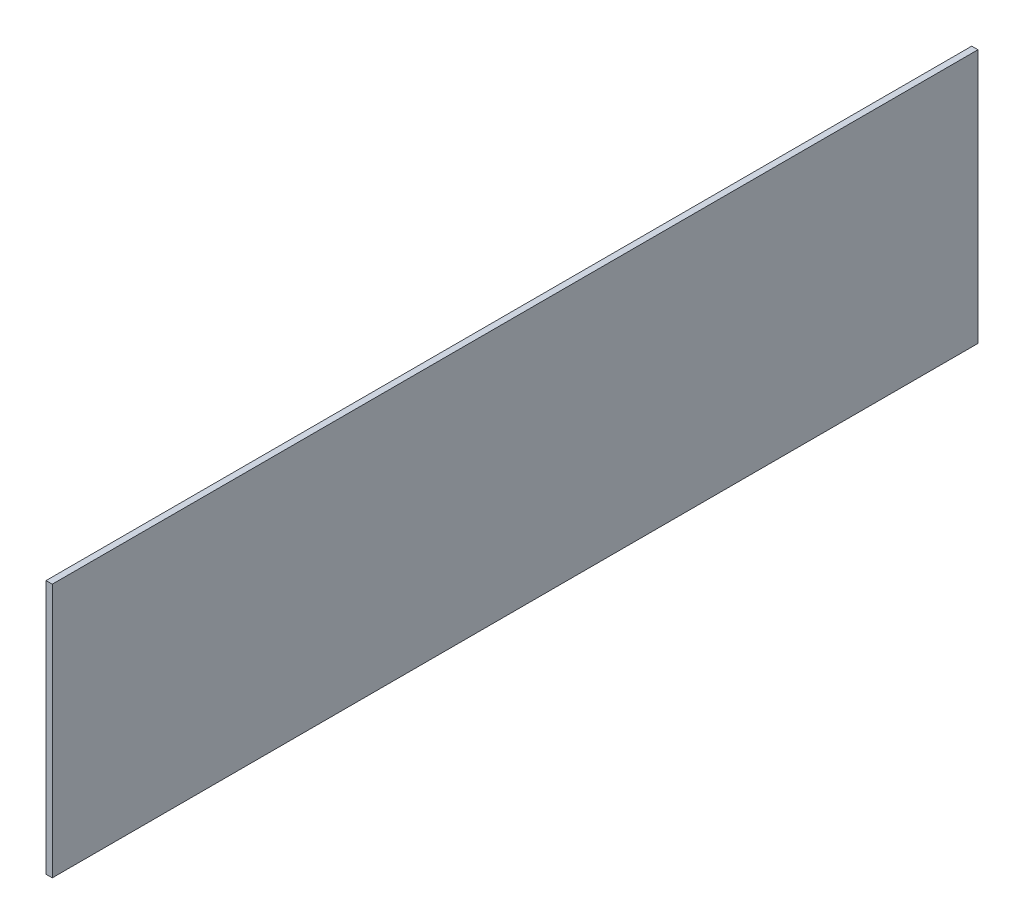
SolidWorks part; units mm, degrees
ref_plane "Front Plane" through (0, 0, 0) normal (0, 0, 1) x (1, 0, 0)
ref_plane "Top Plane" through (0, 0, 0) normal (0, 1, 0) x (1, 0, 0)
ref_plane "Right Plane" through (0, 0, 0) normal (1, 0, 0) x (0, 0, -1)
sketch "Sketch1" plane through (0, 0, 0) normal (0, 0, 1) x (1, 0, 0)
  line L1 (-81.2308, 158.7692) -> (-69.2308, 158.7692)
  line L2 (-81.2308, 158.7692) -> (-81.2308, -329.2308)
  line L3 (-81.2308, -329.2308) -> (-69.2308, -329.2308)
  line L4 (-69.2308, 158.7692) -> (-69.2308, -329.2308)
  dimension "D1" = 12
  dimension "D2" = 488
extrude "Boss-Extrude1" add sketch "Sketch1" along normal blind 1776
